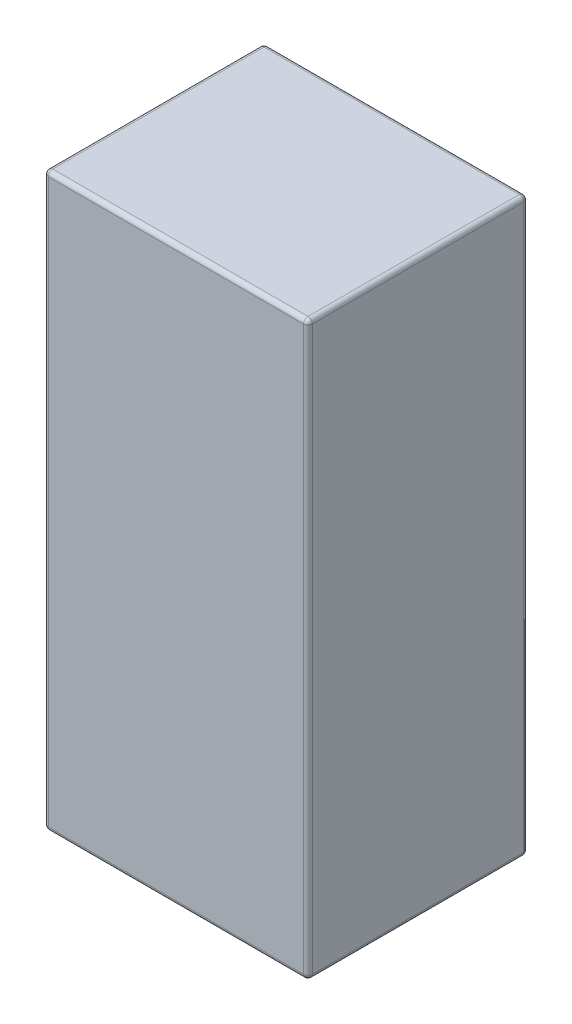
SolidWorks part; units mm, degrees
ref_plane "Front Plane" through (0, 0, 0) normal (1, 0, 0) x (0, 1, 0)
ref_plane "Top Plane" through (0, 0, 0) normal (0, 0, 1) x (0, 1, 0)
ref_plane "Right Plane" through (0, 0, 0) normal (0, 1, 0) x (-1, 0, 0)
sketch "Sketch1" plane through (0, 0, 0) normal (0, 0, 1) x (0, 1, 0)
  line L1 (-6.5, -3) -> (6.5, -3)
  line L2 (-6.5, -3) -> (-6.5, 3)
  line L3 (-6.5, 3) -> (6.5, 3)
  line L4 (6.5, -3) -> (6.5, 3)
  line L5 (-6.5, -3) -> (6.5, 3) construction
  line L6 (-6.5, 3) -> (6.5, -3) construction
  point P0 (0, 0)
  dimension "D1" = 13
  dimension "D2" = 6
extrude "Boss-Extrude1" add sketch "Sketch1" along normal blind 5
fillet "Fillet1" radius 0.1 12 edges at (-3, 6.5, 2.5) (-3, -6.5, 2.5) (3, -6.5, 2.5) (3, 6.5, 2.5) (3, 0, 5) (0, -6.5, 5) (-3, 0, 5) (0, 6.5, 5) (3, 0, 0) (0, -6.5, 0) (-3, 0, 0) (0, 6.5, 0)
